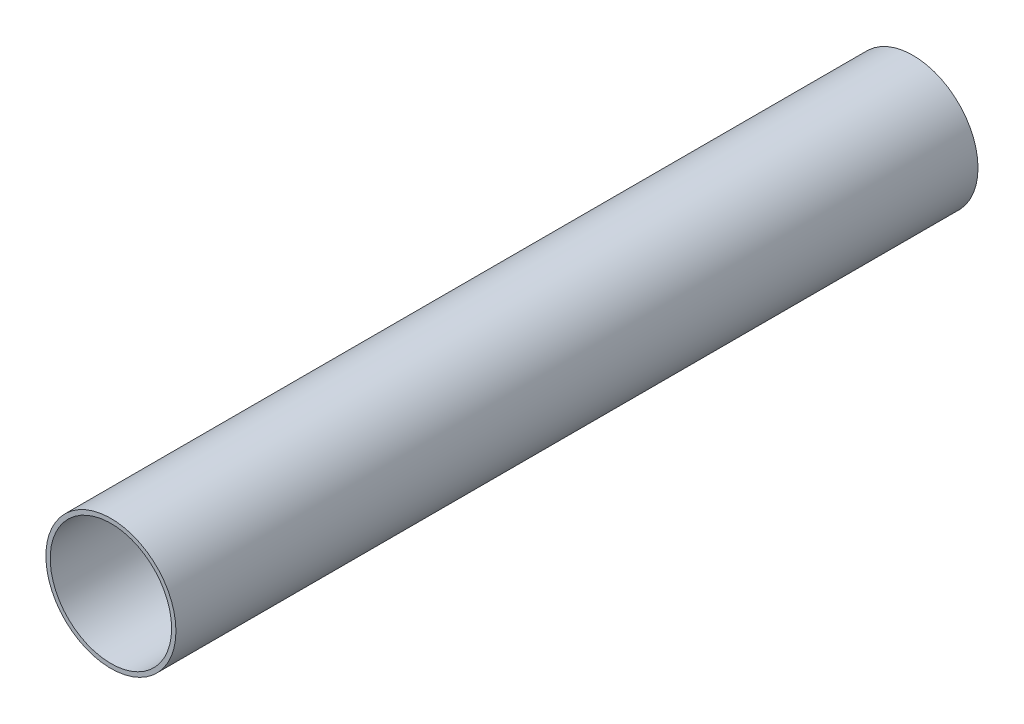
SolidWorks part; units mm, degrees
ref_plane "Front Plane" through (0, 0, 0) normal (0, 0, 1) x (1, 0, 0)
ref_plane "Top Plane" through (0, 0, 0) normal (0, 1, 0) x (1, 0, 0)
ref_plane "Right Plane" through (0, 0, 0) normal (1, 0, 0) x (0, 0, -1)
sketch "Sketch1" plane through (0, 0, 0) normal (0, 0, 1) x (1, 0, 0)
  circle A0 centre (0, 0) radius 15
  circle A1 centre (0, 0) radius 14
  dimension "D1" = 30
  dimension "D2" = 1
extrude "Boss-Extrude1" add sketch "Sketch1" along normal blind 185
